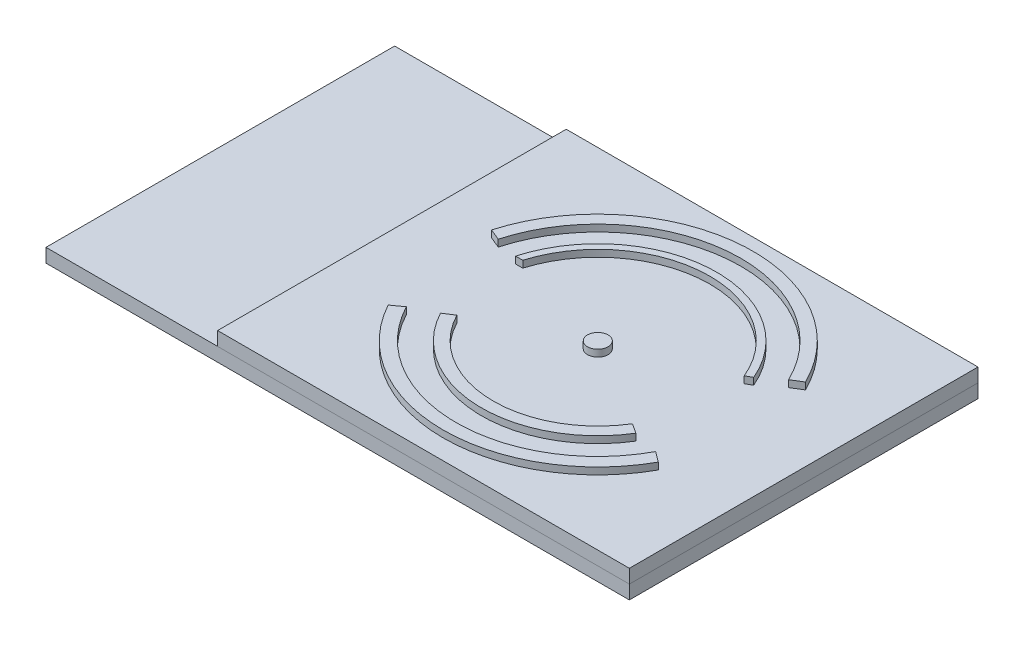
SolidWorks part; units mm, degrees
ref_plane "Front Plane" through (0, 0, 0) normal (0, 0, 1) x (1, 0, 0)
ref_plane "Top Plane" through (0, 0, 0) normal (0, 1, 0) x (1, 0, 0)
ref_plane "Right Plane" through (0, 0, 0) normal (1, 0, 0) x (0, 0, -1)
sketch "Sketch1" plane through (0, 0, 0) normal (0, 1, 0) x (1, 0, 0)
  line L1 (-21.25, -12.7) -> (21.25, -12.7)
  line L2 (-21.25, -12.7) -> (-21.25, 12.7)
  line L3 (-21.25, 12.7) -> (21.25, 12.7)
  line L4 (21.25, -12.7) -> (21.25, 12.7)
  dimension "D1" = 42.5
  dimension "D2" = 25.4
  dimension "D3" = 21.25
  dimension "D4" = 12.7
extrude "Boss-Extrude1" add sketch "Sketch1" along normal blind 1
sketch "Sketch2" plane through (0, 1, 0) normal (0, 1, 0) x (1, 0, 0)
  line L0 (-21.25, -12.7) -> (21.25, -12.7) construction
  line L1 (21.25, 12.7) -> (-8.75, 12.7)
  line L2 (21.25, 12.7) -> (21.25, -12.7)
  line L3 (21.25, -12.7) -> (-8.75, -12.7)
  line L4 (-8.75, 12.7) -> (-8.75, -12.7)
  dimension "D1" = 30
extrude "Boss-Extrude2" add sketch "Sketch2" along normal blind 1 separate body
sketch "Sketch3" plane through (0, 2, 0) normal (0, 1, 0) x (1, 0, 0)
  line L1 (21.25, -12.7) -> (21.25, 12.7) construction
  line L2 (-8.75, -12.7) -> (21.25, -12.7) construction
  line L3 (-4.6178, 3.1271) -> (-3.7901, 2.7881)
  line L4 (-2.0911, 2.3524) -> (-1.5683, 2.3524)
  line L5 (13.792, 3.1271) -> (14.2333, 3.3726)
  line L6 (15.65, 4.4961) -> (16.4099, 4.9663)
  line L7 (12.7464, -3.9643) -> (13.4612, -4.4435)
  line L8 (15.3451, -4.8791) -> (16.1049, -5.4455)
  line L9 (-1.2266, -3.9808) -> (-0.502, -3.5113)
  line L10 (-2.8747, -4.8235) -> (-3.6423, -5.3773)
  circle A0 centre (6.25, 0) radius 0.75
  arc A1 (-1.5683, 2.3524) -> (13.792, 3.1271) centre (6.25, 0) cw
  arc A2 (-2.0911, 2.3524) -> (14.2333, 3.3726) centre (6.25, 0) cw
  arc A3 (-3.7901, 2.7881) -> (15.65, 4.4961) centre (6.25, 0) cw
  arc A4 (-4.6178, 3.1271) -> (16.4099, 4.9663) centre (6.25, 0) cw
  arc A5 (13.4612, -4.4435) -> (-1.2266, -3.9808) centre (6.25, 0) cw
  arc A6 (12.7464, -3.9643) -> (-0.502, -3.5113) centre (6.25, 0) cw
  arc A7 (15.3451, -4.8791) -> (-2.8747, -4.8235) centre (6.25, 0) cw
  arc A8 (16.1049, -5.4455) -> (-3.6423, -5.3773) centre (6.25, 0) cw
  dimension "D1" = 15
  dimension "D3" = 1.5
  dimension "D2" = 12.7
extrude "Boss-Extrude3" add sketch "Sketch3" along normal blind 0.5 separate body
